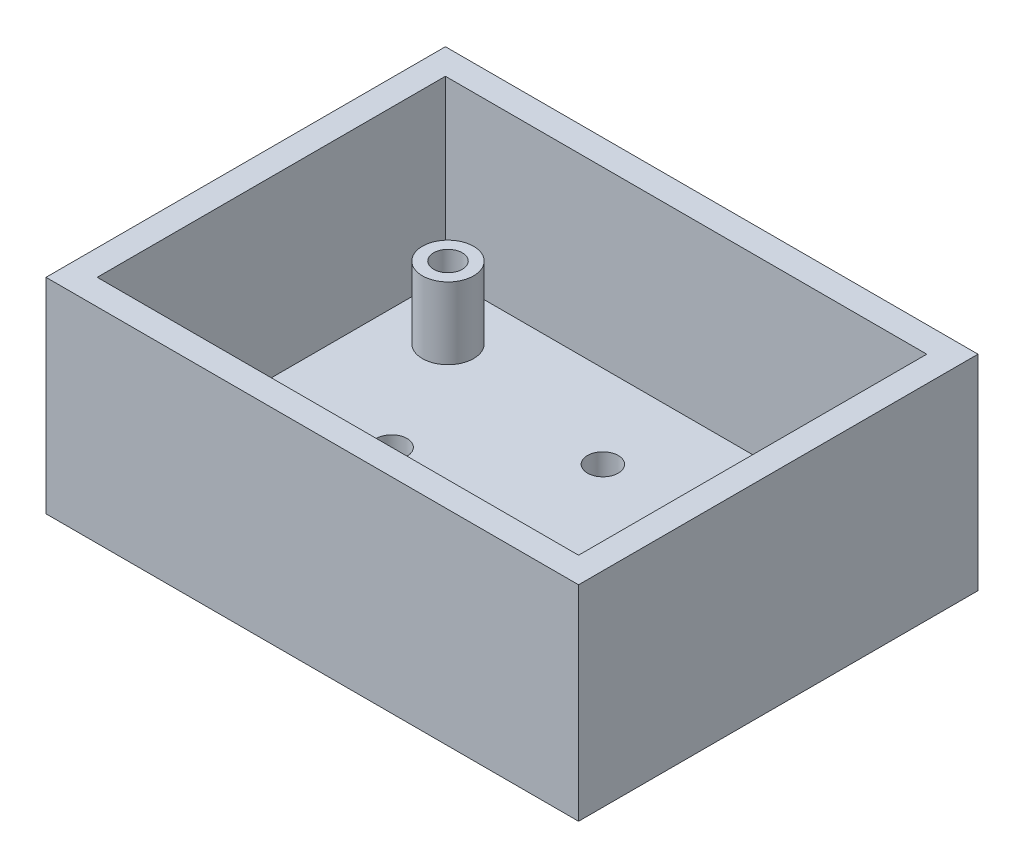
SolidWorks part; units mm, degrees
ref_plane "前视基准面" through (0, 0, 0) normal (0, 0, 1) x (1, 0, 0)
ref_plane "上视基准面" through (0, 0, 0) normal (0, 1, 0) x (1, 0, 0)
ref_plane "右视基准面" through (0, 0, 0) normal (1, 0, 0) x (0, 0, -1)
sketch "草图1" plane through (0, 0, 0) normal (0, 1, 0) x (1, 0, 0)
  line L1 (-23.5, 17) -> (23.5, 17)
  line L2 (-23.5, 17) -> (-23.5, -17)
  line L3 (-23.5, -17) -> (23.5, -17)
  line L4 (23.5, 17) -> (23.5, -17)
  line L5 (-23.5, 17) -> (23.5, -17) construction
  line L6 (-23.5, -17) -> (23.5, 17) construction
  line L7 (-26, 19.5) -> (26, 19.5)
  line L8 (-26, 19.5) -> (-26, -19.5)
  line L9 (-26, -19.5) -> (26, -19.5)
  line L10 (26, 19.5) -> (26, -19.5)
  line L11 (-26, 19.5) -> (26, -19.5) construction
  line L12 (-26, -19.5) -> (26, 19.5) construction
  point P0 (0, 0)
  point P6 (0, 0)
  dimension "D1" = 47
  dimension "D2" = 34
  dimension "D3" = 39
  dimension "D4" = 52
extrude "凸台-拉伸1" add sketch "草图1" along normal blind 20
sketch "草图2" plane through (0, 0, 0) normal (0, -1, 0) x (1, 0, 0)
  line L1 (-17.75, 11.5) -> (17.75, 11.5) construction
  line L2 (-17.75, 11.5) -> (-17.75, -11.5) construction
  line L3 (-17.75, -11.5) -> (17.75, -11.5) construction
  line L4 (17.75, 11.5) -> (17.75, -11.5) construction
  line L5 (-17.75, 11.5) -> (17.75, -11.5) construction
  line L6 (-17.75, -11.5) -> (17.75, 11.5) construction
  circle A0 centre (-17.75, 11.5) radius 2.5
  circle A1 centre (17.75, 11.5) radius 2.5
  circle A2 centre (-17.75, -11.5) radius 2.5
  circle A3 centre (17.75, -11.5) radius 2.5
  point P0 (0, 0)
  dimension "D3" = 5
  dimension "D4" = 5
  dimension "D5" = 5
  dimension "D6" = 5
  dimension "D1" = 35.5
  dimension "D2" = 23
extrude "凸台-拉伸2" add sketch "草图2" against normal blind 10 separate body
sketch "草图3" plane through (0, 10, 0) normal (0, 1, 0) x (1, 0, 0)
  circle A0 centre (-17.75, 11.5) radius 1.4
  circle A1 centre (17.75, 11.5) radius 1.4
  circle A2 centre (-17.75, -11.5) radius 1.4
  circle A3 centre (17.75, -11.5) radius 1.4
  dimension "D1" = 2.8
  dimension "D2" = 2.8
  dimension "D3" = 2.8
  dimension "D4" = 2.8
extrude "切除-拉伸1" cut sketch "草图3" against normal blind 7
sketch "草图4" plane through (0, 0, 0) normal (0, -1, 0) x (1, 0, 0)
  line L1 (-26, 19.5) -> (26, 19.5)
  line L2 (-26, 19.5) -> (-26, -19.5)
  line L3 (-26, -19.5) -> (26, -19.5)
  line L4 (26, 19.5) -> (26, -19.5)
  line L5 (-26, 19.5) -> (26, -19.5) construction
  line L6 (-26, -19.5) -> (26, 19.5) construction
  point P0 (0, 0)
extrude "凸台-拉伸3" add sketch "草图4" against normal blind 3
sketch "草图5" plane through (0, 3, 0) normal (0, 1, 0) x (1, 0, 0)
  line L0 (0, 0) -> (0, 17.7447) construction
  line L1 (0, 0) -> (23.5, 0) construction
  line L2 (23.5, -17) -> (23.5, 17) construction
  circle A0 centre (0, 8.8724) radius 1.5
  circle A1 centre (11.75, 0) radius 1.5
  circle A2 centre (0, -8.8724) radius 1.5
  circle A3 centre (-11.75, 0) radius 1.5
  dimension "D1" = 3
  dimension "D2" = 3
extrude "切除-拉伸2" cut sketch "草图5" against normal through all
